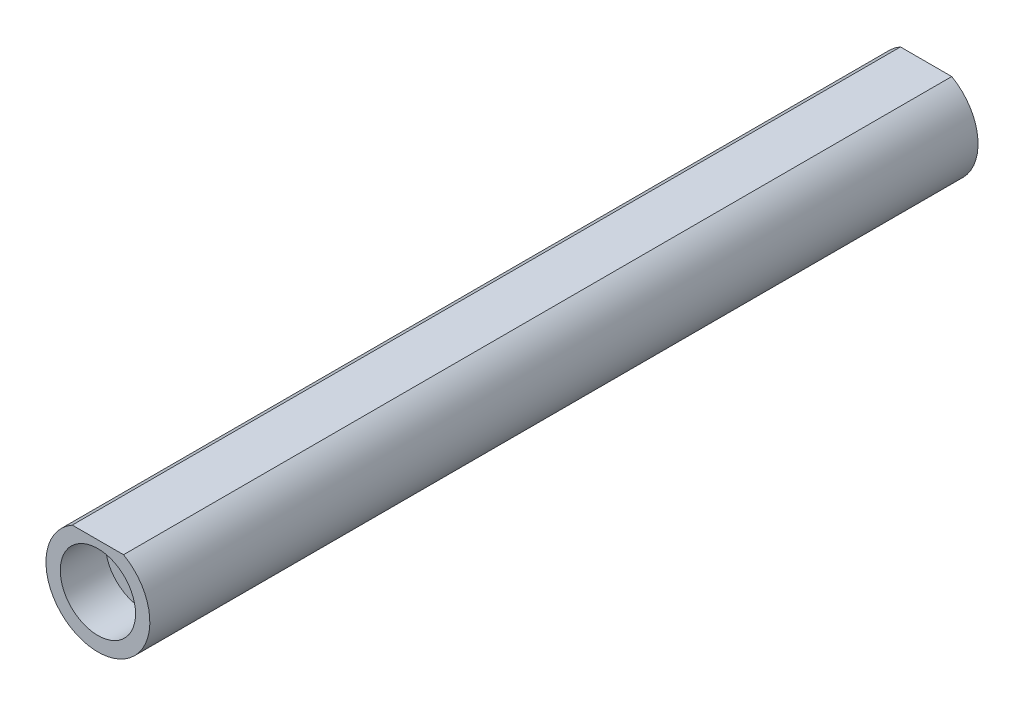
SolidWorks part; units mm, degrees
ref_plane "Front Plane" through (0, 0, 0) normal (0, 0, 1) x (1, 0, 0)
ref_plane "Top Plane" through (0, 0, 0) normal (0, 1, 0) x (1, 0, 0)
ref_plane "Right Plane" through (0, 0, 0) normal (1, 0, 0) x (0, 0, -1)
sketch "Sketch1" plane through (0, 0, 0) normal (0, 0, 1) x (1, 0, 0)
  line L0 (-1.7037, 3) -> (1.7037, 3)
  arc A0 (-1.7037, 3) -> (1.7037, 3) centre (0, 0) ccw
  dimension "D1" = 3.45
  dimension "D2" = 3
extrude "Boss-Extrude2" add sketch "Sketch1" along normal blind 55
sketch "Sketch2" plane through (0, 0, 55) normal (0, 0, 1) x (1, 0, 0)
  circle A0 centre (0, 0) radius 2.5
  dimension "D1" = 5
extrude "Cut-Extrude1" cut sketch "Sketch2" against normal blind 3
